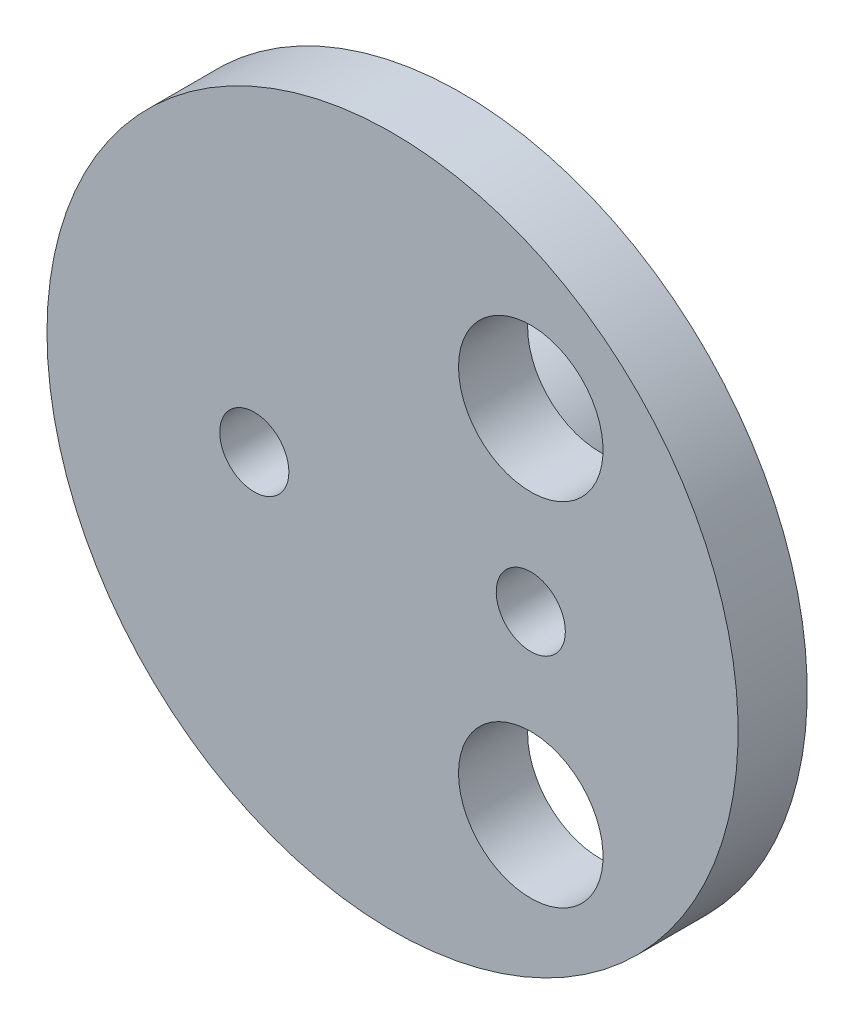
SolidWorks part; units mm, degrees
material "Alliage 6061"
ref_plane "Plan de face" through (0, 0, 0) normal (0, 0, 1) x (1, 0, 0)
ref_plane "Plan de dessus" through (0, 0, 0) normal (0, 1, 0) x (1, 0, 0)
ref_plane "Plan de droite" through (0, 0, 0) normal (1, 0, 0) x (0, 0, -1)
sketch "Esquisse1" plane through (0, 0, 0) normal (0, 0, 1) x (1, 0, 0)
  circle A0 centre (0, 0) radius 12.5
  circle A1 centre (5, 0) radius 1.25
  circle A2 centre (-5, 0) radius 1.25
  circle A3 centre (5, 6.364) radius 2.614
  circle A4 centre (5, -6.364) radius 2.614
extrude "Disque O25" add sketch "Esquisse1" along normal blind 2.5
sketch "Esquisse2" plane through (0, 0, 0) normal (0, 0, 1) x (1, 0, 0)
  circle A0 centre (0, 0) radius 5
  circle A1 centre (0, 0) radius 2.9
extrude "Moyeu cannele 25T" add sketch "Esquisse2" against normal blind 3.5
